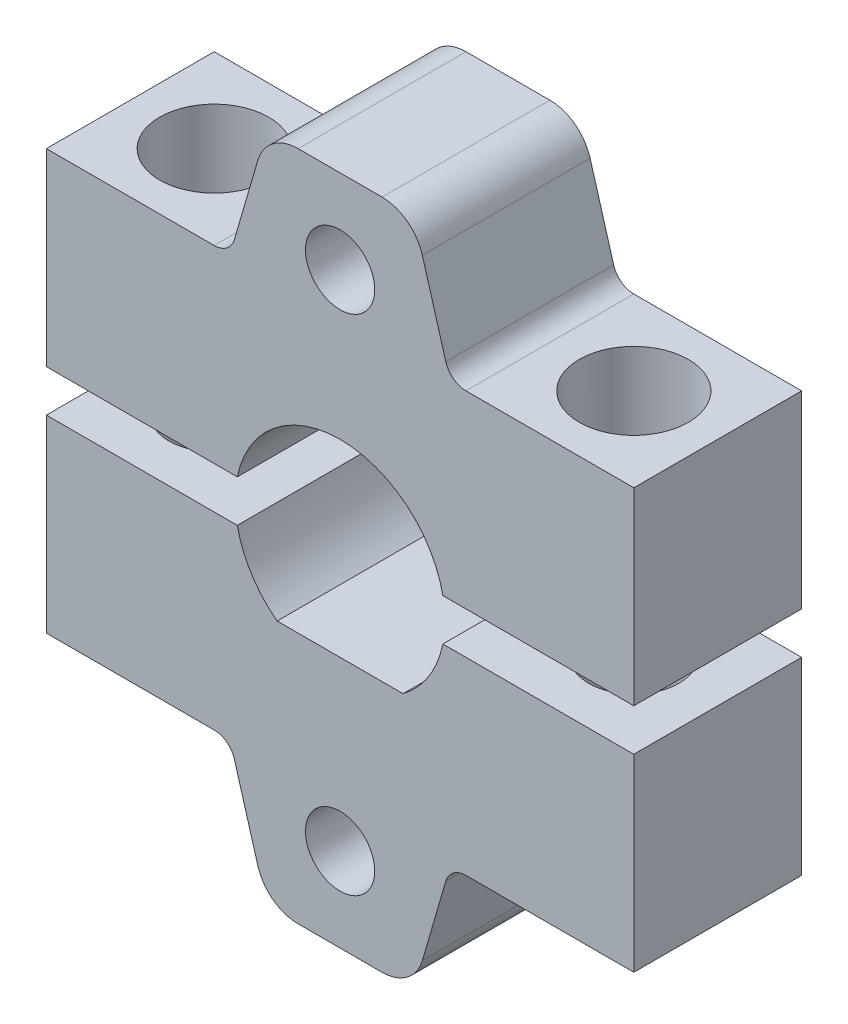
SolidWorks part; units mm, degrees
material "6061 合金"
ref_plane "前视基准面" through (0, 0, 0) normal (0, 0, 1) x (1, 0, 0)
ref_plane "上视基准面" through (0, 0, 0) normal (0, 1, 0) x (1, 0, 0)
ref_plane "右视基准面" through (0, 0, 0) normal (1, 0, 0) x (0, 0, -1)
sketch "草图1" plane through (0, 0, 0) normal (0, 0, 1) x (1, 0, 0)
  line L0 (-3, -4) -> (3, -4)
  line L8 (0, 0) -> (0, -14.8013) construction
  line L13 (-12, 0) -> (12, 0) construction
  line L18 (-3.92, 14.56) -> (-5.04, 10.72)
  line L19 (-6, 10) -> (-14, 10)
  line L20 (0, 16) -> (0, 0) construction
  line L23 (-4.899, 1) -> (-14, 1)
  line L24 (-14, 1) -> (-14, 10)
  line L34 (2, 16) -> (-2, 16)
  line L36 (3.92, 14.56) -> (5.04, 10.72)
  line L37 (6, 10) -> (14, 10)
  line L38 (4.899, 1) -> (14, 1)
  line L39 (14, 1) -> (14, 10)
  line L40 (4.899, -1) -> (14, -1)
  line L41 (14, -1) -> (14, -10)
  line L42 (6, -10) -> (14, -10)
  line L43 (3.92, -14.56) -> (5.04, -10.72)
  line L44 (2, -16) -> (-2, -16)
  line L45 (-3.92, -14.56) -> (-5.04, -10.72)
  line L46 (-6, -10) -> (-14, -10)
  line L47 (-14, -1) -> (-14, -10)
  line L48 (-4.899, -1) -> (-14, -1)
  arc A0 (3, -4) -> (4.899, -1) centre (0, 0) ccw
  circle A1 centre (0, 0) radius 12 construction
  arc A16 (4.899, 1) -> (-4.899, 1) centre (0, 0) ccw
  arc A20 (-3, -4) -> (-4.899, -1) centre (0, 0) cw
  circle A22 centre (0, 12) radius 1.65
  circle A23 centre (0, -12) radius 1.65
  circle A24 centre (0, 0) radius 16 construction
  arc A25 (-5.04, 10.72) -> (-6, 10) centre (-6, 11) cw
  arc A26 (-3.92, 14.56) -> (-2, 16) centre (-2, 14) cw
  arc A27 (3.92, 14.56) -> (2, 16) centre (2, 14) ccw
  arc A28 (5.04, 10.72) -> (6, 10) centre (6, 11) ccw
  arc A29 (5.04, -10.72) -> (6, -10) centre (6, -11) cw
  arc A30 (3.92, -14.56) -> (2, -16) centre (2, -14) cw
  arc A31 (-3.92, -14.56) -> (-2, -16) centre (-2, -14) ccw
  arc A32 (-5.04, -10.72) -> (-6, -10) centre (-6, -11) ccw
  point P19 (0, 0)
  point P26 (0, -4)
  point P44 (-5, 10)
  point P47 (-4, 16)
  dimension "D1" = 10
  dimension "D3" = 24
  dimension "D5" = 16
  dimension "D6" = 1
  dimension "D7" = 14
  dimension "D4" = 3.3
  dimension "D9" = 32
  dimension "D8" = 1
  dimension "D13" = 2
  dimension "D2" = 4
  dimension "D10" = 4
  dimension "D11" = 10
  dimension "D12" = 9
  dimension "D14" = 8
  dimension "D15" = 2
extrude "凸台-拉伸1" add sketch "草图1" along normal blind 8
cosmetic thread "装饰螺纹线7" parameters "D2"=4
cosmetic thread "装饰螺纹线8" parameters "D2"=4
sketch "草图3" plane through (0, 10, 0) normal (0, 1, 0) x (1, 0, 0)
  line L0 (10, -4) -> (-10, -4) construction
  line L1 (0, -8) -> (0, -4) construction
  line L3 (0, -4) -> (0, 0) construction
  line L5 (14, 0) -> (6, 0) construction
  circle A0 centre (10, -4) radius 2.6
  circle A1 centre (-10, -4) radius 2.6
  dimension "D1" = 5.2
  dimension "D2" = 20
  dimension "D3" = 4
extrude "切除-拉伸2" cut sketch "草图3" against normal up to next (9 mm away) and the other way through all
sketch "草图4" plane through (0, -10, 0) normal (0, 1, 0) x (1, 0, 0)
  circle A0 centre (10, -4) radius 2.15
  circle A1 centre (-10, -4) radius 2.15
  dimension "D1" = 4.3
extrude "切除-拉伸3" cut sketch "草图4" along normal through all
cosmetic thread "装饰螺纹线5" parameters "D2"=5
cosmetic thread "装饰螺纹线6" parameters "D2"=5
